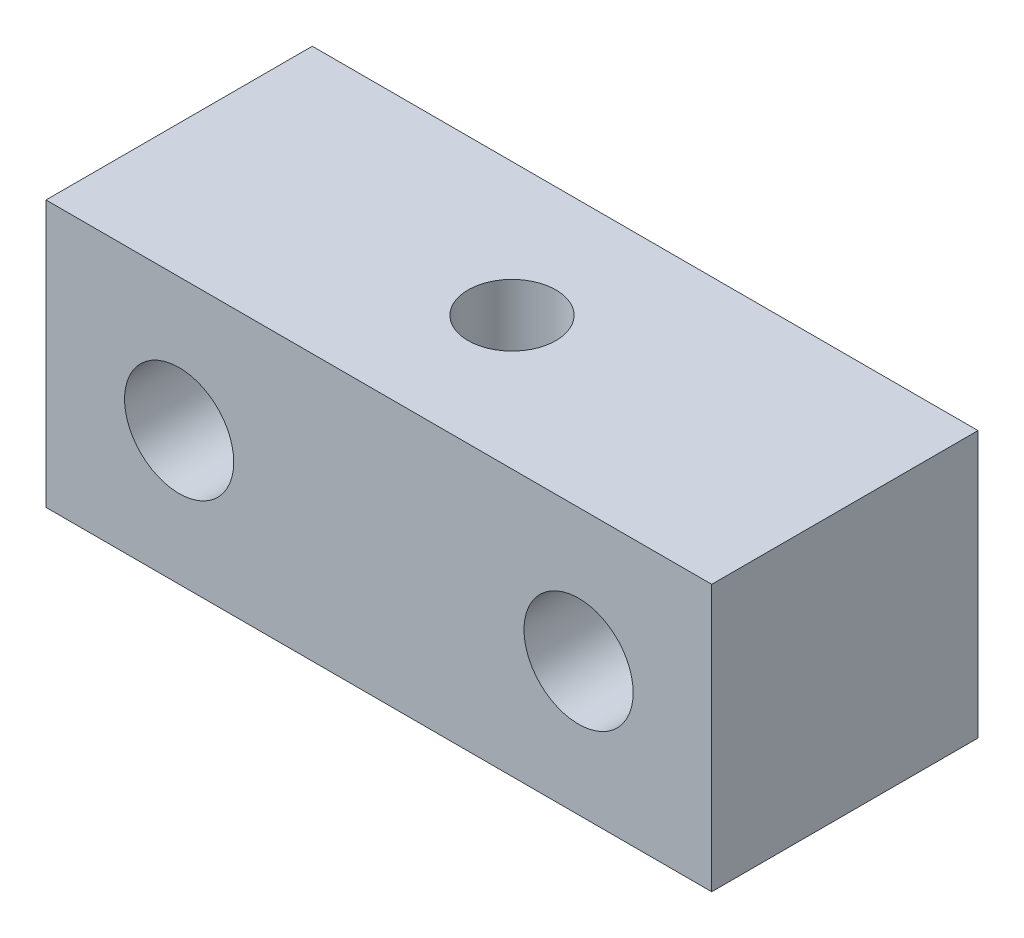
SolidWorks part; units mm, degrees
material "6061 合金"
ref_plane "前视基准面" through (0, 0, 0) normal (0, 0, 1) x (1, 0, 0)
ref_plane "上视基准面" through (0, 0, 0) normal (0, 1, 0) x (1, 0, 0)
ref_plane "右视基准面" through (0, 0, 0) normal (1, 0, 0) x (0, 0, -1)
other "Configuration Table"
sketch "草图1" plane through (0, 0, 0) normal (1, 0, 0) x (0, 0, -1)
  line L1 (-5, -5) -> (5, -5)
  line L2 (-5, -5) -> (-5, 5)
  line L3 (-5, 5) -> (5, 5)
  line L4 (5, -5) -> (5, 5)
  line L5 (-5, -5) -> (5, 5) construction
  line L6 (-5, 5) -> (5, -5) construction
  point P0 (0, 0)
  dimension "D1" = 10
extrude "凸台-拉伸1" add sketch "草图1" along normal blind 25
sketch "草图2" plane through (0, 5, 0) normal (0, 1, 0) x (1, 0, 0)
  line L0 (-0.9079, 0) -> (25.6737, 0) construction
  line L1 (25, 5) -> (25, -5) construction
  circle A0 centre (12.5, 0) radius 1.5
  dimension "D1" = 12.5
  dimension "D2" = 3
extrude "切除-拉伸1" cut sketch "草图2" against normal through all
sketch "草图3" plane through (0, 0, 5) normal (0, 0, 1) x (1, 0, 0)
  line L0 (-1.4867, 0) -> (26.1009, 0) construction
  line L1 (0, 5) -> (0, -5) construction
  line L2 (25, 5) -> (25, -5) construction
  circle A0 centre (5, 0) radius 2.05
  circle A1 centre (20, 0) radius 2.05
  dimension "D1" = 5
  dimension "D2" = 5
  dimension "D3" = 4.1
extrude "切除-拉伸2" cut sketch "草图3" against normal through all
sketch "草图5" plane through (0, 5, 0) normal (0, 1, 0) x (1, 0, 0)
  circle A0 centre (12.5, 0) radius 2
  point P0 (12.5, 0)
  dimension "D1" = 4
hole_wizard "M4 螺纹孔2" positions "草图5" profile "草图7" tap size "M4" standard "GB"
sketch "草图7" plane through (12.5, 5, 0) normal (1, 0, 0) x (0, 0, 1)
  line L0 (0, 0) -> (0, 11.0914)
  line L1 (0, 11.0914) -> (1.65, 10.1)
  line L2 (1.65, 10.1) -> (1.65, 0)
  line L5 (1.65, 0) -> (0, 0)
  line L10 (0, 11.0914) -> (-1.65, 10.1) construction
  line L11 (0, -6.35) -> (0, 107.95) construction
  dimension "螺纹孔钻头直径" = 3.3
  dimension "螺纹孔钻头深度" = 10.1
  dimension "导头角度" = 118
cosmetic thread "孔螺纹线1" parameters "D1"=8, "D2"=4
